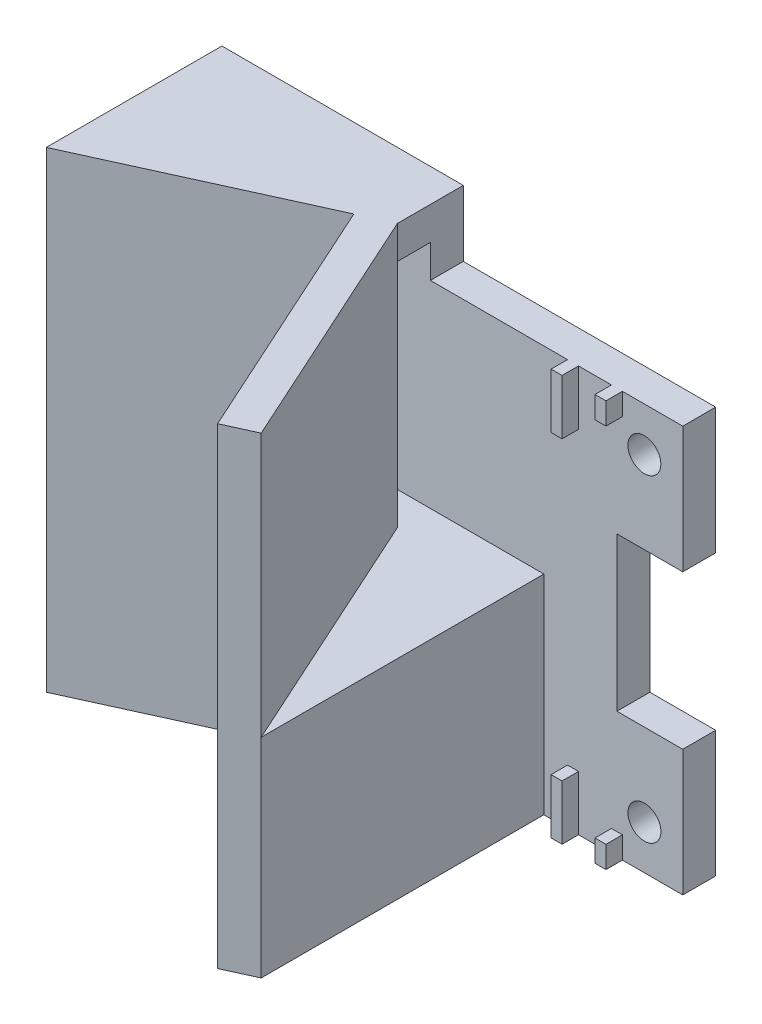
SolidWorks part; units mm, degrees
ref_plane "Alzado" through (0, 0, 0) normal (0, 0, 1) x (1, 0, 0)
ref_plane "Planta" through (0, 0, 0) normal (0, 1, 0) x (1, 0, 0)
ref_plane "Vista lateral" through (0, 0, 0) normal (1, 0, 0) x (0, 0, -1)
sketch "Croquis1" plane through (0, 0, 0) normal (0, 0, 1) x (1, 0, 0)
  line L1 (-52.1973, 33.4619) -> (-4.1973, 33.4619)
  line L2 (-56.1973, 29.4619) -> (-56.1973, 0.4619)
  line L3 (-52.4067, -3.5381) -> (-4.1973, -3.5381)
  line L4 (-4.1973, 33.4619) -> (-4.1973, -3.5381)
  line L5 (-56.1973, 24.9619) -> (-49.1973, 24.9619)
  line L6 (-56.1973, 24.9619) -> (-56.1973, 4.9619)
  line L7 (-56.1973, 4.9619) -> (-49.1973, 4.9619)
  line L8 (-49.1973, 24.9619) -> (-49.1973, 4.9619)
  line L9 (-4.1973, 21.9619) -> (-10.1973, 21.9619)
  line L10 (-4.1973, 21.9619) -> (-4.1973, 7.9619)
  line L11 (-4.1973, 7.9619) -> (-10.1973, 7.9619)
  line L12 (-10.1973, 21.9619) -> (-10.1973, 7.9619)
  circle A0 centre (-52.1973, 29.4619) radius 1.5
  circle A1 centre (-7.6973, 29.4619) radius 1.5
  circle A2 centre (-52.1915, 0.4619) radius 1.5
  circle A3 centre (-7.6915, 0.4619) radius 1.5
  arc A4 (-56.1973, 29.4619) -> (-52.1973, 33.4619) centre (-52.1973, 29.4619) cw
  arc A5 (-52.4067, -3.5381) -> (-56.1973, 0.4619) centre (-52.1915, 0.4619) cw
  dimension "D3" = 4
  dimension "D5" = 44.5
  dimension "D6" = 4
  dimension "D7" = 29
  dimension "D1" = 8.5
  dimension "D2" = 20
  dimension "D4" = 4
  dimension "D8" = 4
  dimension "D9" = 44.5
  dimension "D10" = 7
  dimension "D11" = 11.5
  dimension "D12" = 6
  dimension "D13" = 14
  dimension "D14" = 48
extrude "Saliente-Extruir1" add sketch "Croquis1" along normal blind 3 contours A5 L3 L4 L11 L12 L9 L1 A4 L2 L5 L8 L7 A3 A2 A1 A0
sketch "Croquis3" plane through (0, 0, 3) normal (0, 0, 1) x (1, 0, 0)
  line L0 (-52.1973, 33.4619) -> (-4.1973, 33.4619) construction
  line L1 (-49.1973, 33.4619) -> (-27.1973, 33.4619)
  line L2 (-49.1973, 33.4619) -> (-49.1973, -3.5381)
  line L3 (-49.1973, -3.5381) -> (-27.1973, -3.5381)
  line L4 (-27.1973, 33.4619) -> (-27.1973, -3.5381)
  line L5 (-52.4067, -3.5381) -> (-4.1973, -3.5381) construction
  circle A0 centre (-52.1973, 29.4619) radius 1.5 construction
  dimension "D1" = 3
  dimension "D2" = 22
extrude "Saliente-Extruir2" add sketch "Croquis3" along normal blind 13
sketch "Croquis4" plane through (0, -3.5381, 0) normal (0, -1, 0) x (1, 0, 0)
  line L0 (-27.1973, 16) -> (-27.1973, 6.0021)
  line L1 (-27.1973, 16) -> (-27.1973, 3) construction
  line L2 (-27.1973, 16) -> (-49.1973, 16)
  line L7 (-27.1973, 6.0021) -> (-49.1973, 16)
  line L8 (-27.1973, 3) -> (-4.1973, 3) construction
  dimension "D1" = 3.0021
extrude "Cortar-Extruir1" cut sketch "Croquis4" against normal up to vertex
sketch "Croquis6" plane through (0, 33.4619, 0) normal (0, 1, 0) x (1, 0, 0)
  line L0 (-27.1973, -6.0021) -> (-49.1973, -16)
  line L1 (-49.1973, -16) -> (-49.1973, 0)
  line L2 (-52.1973, 0) -> (-4.1973, 0) construction
  line L3 (-49.1973, 0) -> (-27.1973, 0)
  line L4 (-27.1973, 0) -> (-27.1973, -6.0021)
extrude "Saliente-Extruir4" add sketch "Croquis6" along normal blind 6
sketch "Croquis7" plane through (-27.1973, 0, 0) normal (1, 0, 0) x (0, 0, -1)
  line L0 (-6.0021, 39.4619) -> (-6.0021, -3.5381) construction
  line L1 (-6.0021, 15.4619) -> (-3, 15.4619)
  line L2 (-6.0021, 15.4619) -> (-6.0021, 36.4619)
  line L3 (-6.0021, 36.4619) -> (-3, 36.4619)
  line L4 (-3, 15.4619) -> (-3, 36.4619)
  line L5 (-6.0021, -3.5381) -> (-3, -3.5381) construction
  line L6 (-6.0021, 39.4619) -> (0, 39.4619) construction
  dimension "D1" = 19
  dimension "D2" = 3
extrude "Cortar-Extruir2" cut sketch "Croquis7" against normal up to vertex (22 mm away)
sketch "Croquis8" plane through (-2.3947, 0, -5.2695) normal (0.4137, 0, 0.9104) x (0.9104, 0, -0.4137)
  line L0 (-51.4089, 39.4619) -> (-27.2436, 39.4619) construction
  line L1 (-27.2436, -3.5381) -> (-30.2436, -3.5381)
  line L2 (-27.2436, -3.5381) -> (-27.2436, 39.4619)
  line L3 (-27.2436, 39.4619) -> (-30.2436, 39.4619)
  line L4 (-30.2436, -3.5381) -> (-30.2436, 39.4619)
  dimension "D1" = 3
extrude "Saliente-Extruir5" add sketch "Croquis8" along normal blind 25
sketch "Croquis9" plane through (0, -3.5381, 0) normal (0, -1, 0) x (1, 0, 0)
  line L0 (-16.854, 28.762) -> (-27.1973, 6.0021)
  line L1 (-27.1973, 6.0021) -> (-27.1973, 3)
  line L2 (-27.1973, 3) -> (-16.854, 3)
  line L3 (-27.1973, 3) -> (-4.1973, 3) construction
  line L4 (-16.854, 3) -> (-16.854, 28.762)
extrude "Saliente-Extruir6" add sketch "Croquis9" against normal up to vertex
sketch "Croquis13" plane through (0, 0, 3) normal (0, 0, 1) x (1, 0, 0)
  line L0 (-16.854, -3.5381) -> (-4.1973, -3.5381) construction
  line L1 (-10.6973, -3.5381) -> (-9.6973, -3.5381)
  line L2 (-10.6973, -3.5381) -> (-10.6973, -1.5381)
  line L3 (-10.6973, -1.5381) -> (-9.6973, -1.5381)
  line L4 (-9.6973, -3.5381) -> (-9.6973, -1.5381)
  line L5 (-4.1973, 7.9619) -> (-4.1973, -3.5381) construction
  line L6 (-10.6973, 31.4619) -> (-9.6973, 31.4619)
  line L7 (-10.6973, 31.4619) -> (-10.6973, 33.4619)
  line L8 (-10.6973, 33.4619) -> (-9.6973, 33.4619)
  line L9 (-9.6973, 31.4619) -> (-9.6973, 33.4619)
  line L10 (-13.6973, 28.4619) -> (-14.6973, 28.4619)
  line L11 (-13.6973, -3.5381) -> (-14.6973, -3.5381)
  line L12 (-13.6973, -3.5381) -> (-13.6973, 1.4619)
  line L13 (-13.6973, 1.4619) -> (-14.6973, 1.4619)
  line L14 (-14.6973, -3.5381) -> (-14.6973, 1.4619)
  line L15 (-13.6973, 28.4619) -> (-13.6973, 33.4619)
  line L16 (-13.6973, 33.4619) -> (-14.6973, 33.4619)
  line L17 (-14.6973, 28.4619) -> (-14.6973, 33.4619)
  dimension "D1" = 5.5
  dimension "D2" = 1
  dimension "D3" = 2
  dimension "D5" = 5
  dimension "D6" = 1
  dimension "D7" = 3
  dimension "D4" = 2
  dimension "D8" = 2
extrude "Saliente-Extruir8" add sketch "Croquis13" along normal blind 1.5
